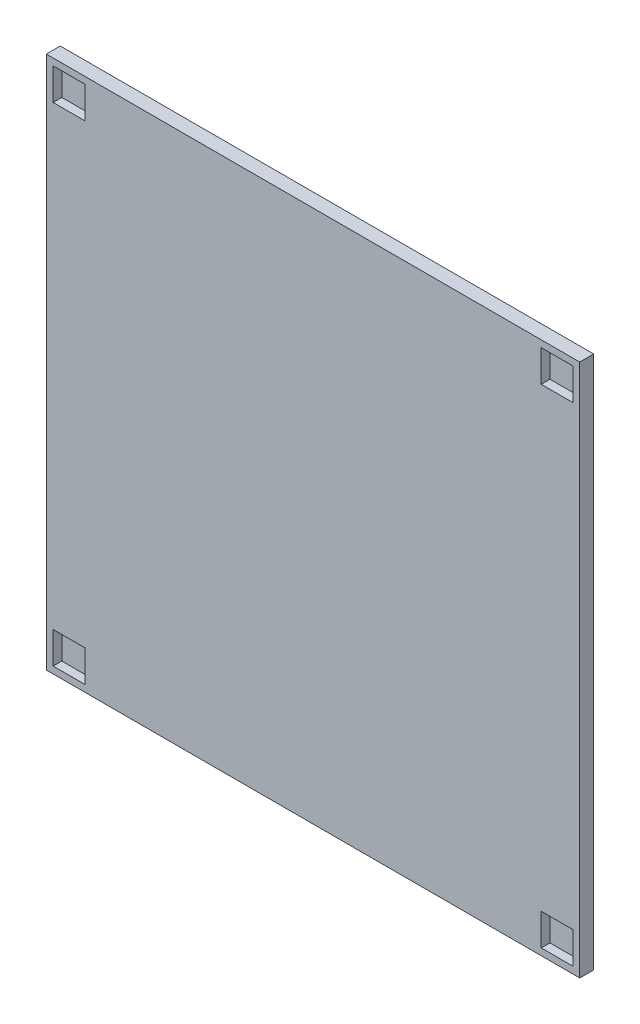
SolidWorks part; units mm, degrees
material "ABS"
ref_plane "Front Plane" through (0, 0, 0) normal (0, 0, 1) x (1, 0, 0)
ref_plane "Top Plane" through (0, 0, 0) normal (0, 1, 0) x (1, 0, 0)
ref_plane "Right Plane" through (0, 0, 0) normal (1, 0, 0) x (0, 0, -1)
sketch "Sketch1" plane through (0, 0, 0) normal (0, 0, 1) x (1, 0, 0)
  line L1 (-153, -153) -> (153, -153)
  line L2 (-153, -153) -> (-153, 153)
  line L3 (-153, 153) -> (153, 153)
  line L4 (153, -153) -> (153, 153)
extrude "Boss-Extrude1" add sketch "Sketch1" along normal blind 8
sketch "Sketch2" plane through (0, 0, 8) normal (0, 0, 1) x (1, 0, 0)
  line L0 (130.9, 130.9) -> (149.1, 130.9)
  line L1 (149.1, 130.9) -> (149.1, 149.1)
  line L2 (149.1, 149.1) -> (130.9, 149.1)
  line L3 (130.9, 149.1) -> (130.9, 130.9)
  line L4 (-149.1, 130.9) -> (-130.9, 130.9)
  line L5 (-130.9, 130.9) -> (-130.9, 149.1)
  line L6 (-130.9, 149.1) -> (-149.1, 149.1)
  line L7 (-149.1, 149.1) -> (-149.1, 130.9)
  line L8 (130.9, -149.1) -> (149.1, -149.1)
  line L9 (149.1, -149.1) -> (149.1, -130.9)
  line L10 (149.1, -130.9) -> (130.9, -130.9)
  line L11 (130.9, -130.9) -> (130.9, -149.1)
  line L12 (-149.1, -149.1) -> (-130.9, -149.1)
  line L13 (-130.9, -149.1) -> (-130.9, -130.9)
  line L14 (-130.9, -130.9) -> (-149.1, -130.9)
  line L15 (-149.1, -130.9) -> (-149.1, -149.1)
extrude "Cut-Extrude1" cut sketch "Sketch2" against normal blind 5
